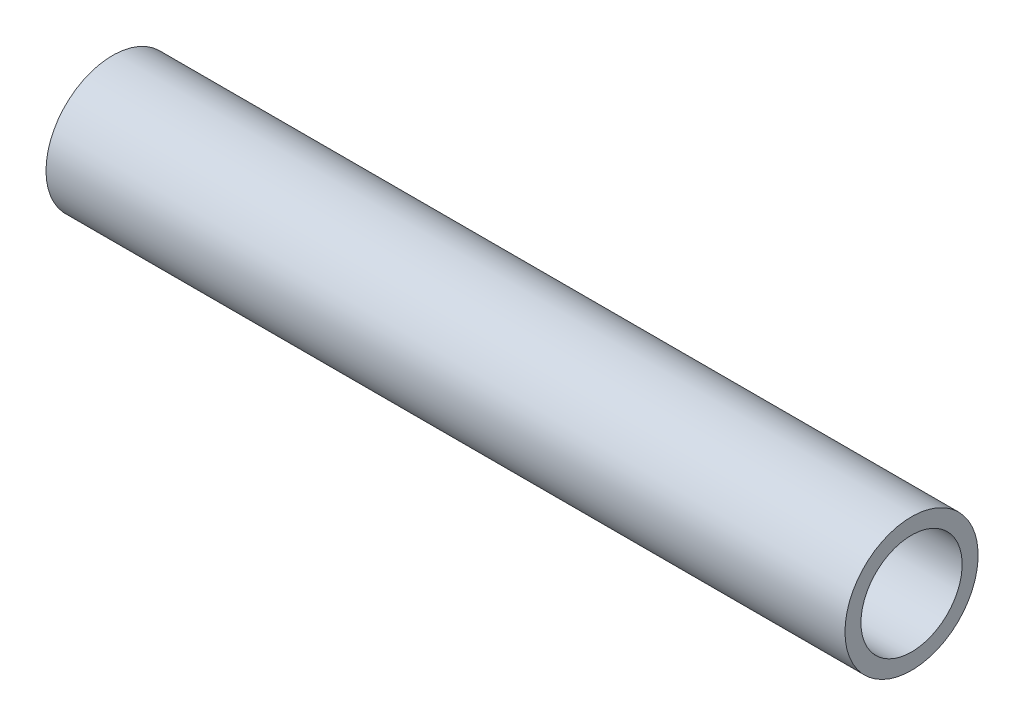
SolidWorks part; units mm, degrees
material "AISI 1010 Steel, hot rolled bar"
ref_plane "Front Plane" through (0, 0, 0) normal (0, 0, 1) x (1, 0, 0)
ref_plane "Top Plane" through (0, 0, 0) normal (0, 1, 0) x (1, 0, 0)
ref_plane "Right Plane" through (0, 0, 0) normal (1, 0, 0) x (0, 0, -1)
sketch "Sketch1" plane through (0, 0, 0) normal (1, 0, 0) x (0, 0, -1)
  circle A0 centre (0, 0) radius 12.7
  circle A1 centre (0, 0) radius 9.652
  dimension "D1" = 25.4
  dimension "D2" = 19.304
extrude "Boss-Extrude1" add sketch "Sketch1" along normal blind 152.4
